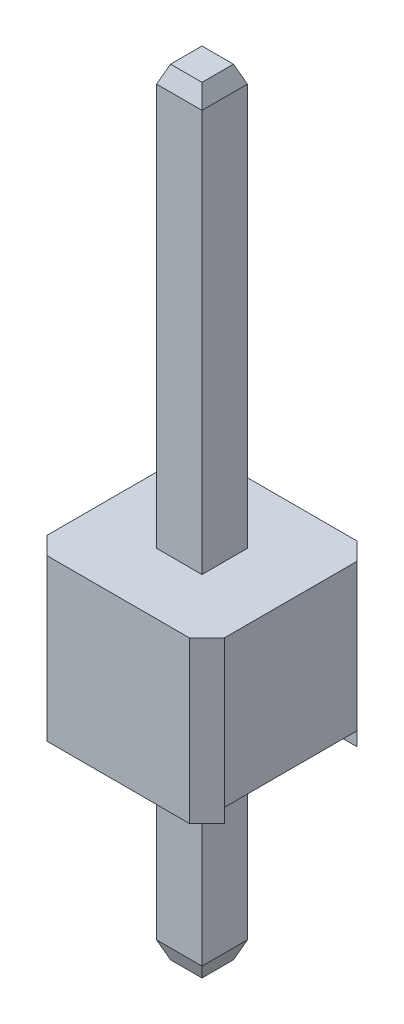
SolidWorks part; units mm, degrees
ref_plane "Alzado" through (0, 0, 0) normal (0, 0, 1) x (1, 0, 0)
ref_plane "Planta" through (0, 0, 0) normal (0, 1, 0) x (1, 0, 0)
ref_plane "Vista lateral" through (0, 0, 0) normal (1, 0, 0) x (0, 0, -1)
ref_plane "Plano1" through (0, 3.2, 0) normal (0, -1, 0) x (1, 0, 0)
sketch "Croquis1" plane through (0, 3.2, 0) normal (0, -1, 0) x (1, 0, 0)
  line L0 (-0.945, 1.525) -> (-0.945, -0.625)
  line L1 (-0.945, -0.625) -> (-0.695, -0.875)
  line L2 (-0.695, -0.875) -> (1.595, -0.875)
  line L3 (1.595, -0.875) -> (1.595, 1.275)
  line L4 (1.595, 1.275) -> (1.345, 1.525)
  line L5 (1.345, 1.525) -> (-0.945, 1.525)
extrude "Saliente-Extruir1" add sketch "Croquis1" against normal blind 2.1
sketch "Croquis2" plane through (0, 3.2, 0) normal (0, -1, 0) x (1, 0, 0)
  line L0 (-0.945, 1.525) -> (1.345, 1.525)
  line L1 (1.345, 1.525) -> (1.595, 1.275)
  line L2 (1.595, 1.275) -> (-0.945, 1.275)
  line L3 (-0.945, 1.275) -> (-0.945, 1.525)
extrude "Saliente-Extruir2" add sketch "Croquis2" along normal blind 0.2
sketch "Croquis3" plane through (0, 3.2, 0) normal (0, -1, 0) x (1, 0, 0)
  line L0 (1.595, -0.875) -> (-0.695, -0.875)
  line L1 (-0.695, -0.875) -> (-0.945, -0.625)
  line L2 (-0.945, -0.625) -> (1.595, -0.625)
  line L3 (1.595, -0.625) -> (1.595, -0.875)
extrude "Saliente-Extruir3" add sketch "Croquis3" along normal blind 0.2
sketch "Croquis4" plane through (0, 3.2, 0) normal (0, -1, 0) x (1, 0, 0)
  line L0 (0.65, 0.65) -> (0.65, 0)
  line L1 (0.65, 0) -> (0, 0)
  line L2 (0, 0) -> (0, 0.65)
  line L3 (0, 0.65) -> (0.65, 0.65)
extrude "Saliente-Extruir4" add sketch "Croquis4" along normal blind 3 separate body
sketch "Croquis5" plane through (0, 5.3, 0) normal (0, 1, 0) x (-1, 0, 0)
  line L0 (0, 0.65) -> (0, 0)
  line L1 (0, 0) -> (-0.65, 0)
  line L2 (-0.65, 0) -> (-0.65, 0.65)
  line L3 (-0.65, 0.65) -> (0, 0.65)
extrude "Saliente-Extruir5" add sketch "Croquis5" along normal blind 6 separate body
chamfer "Chaflán1" distance 0.25 angle 45 2 edges at (-0.945, 4.15, 1.525) (1.595, 4.15, -0.875)
chamfer "Chaflán2" distance 0.1 angle 68 4 edges at (0.325, 0.2, 0) (0.65, 0.2, 0.325) (0, 0.2, 0.325) (0.325, 0.2, 0.65)
chamfer "Chaflán3" distance 0.1 angle 68 4 edges at (0, 11.3, 0.325) (0.325, 11.3, 0.65) (0.325, 11.3, 0) (0.65, 11.3, 0.325)
sketch "Croquis6" plane through (0, 0.2, 0) normal (0, -1, 0) x (1, 0, 0)
  line L0 (0.325, 0.55) -> (0.325, 0.325) construction
  line L1 (0.55, 0.55) -> (0.1, 0.55) construction
  line L2 (0.325, 0.325) -> (0.1, 0.325) construction
  line L3 (0.1, 0.55) -> (0.1, 0.1) construction
  line L4 (0.325, 0.325) -> (0.325, 0.1) construction
  line L5 (0.1, 0.1) -> (0.55, 0.1) construction
  circle A0 centre (0.325, 0.325) radius 0.3249
